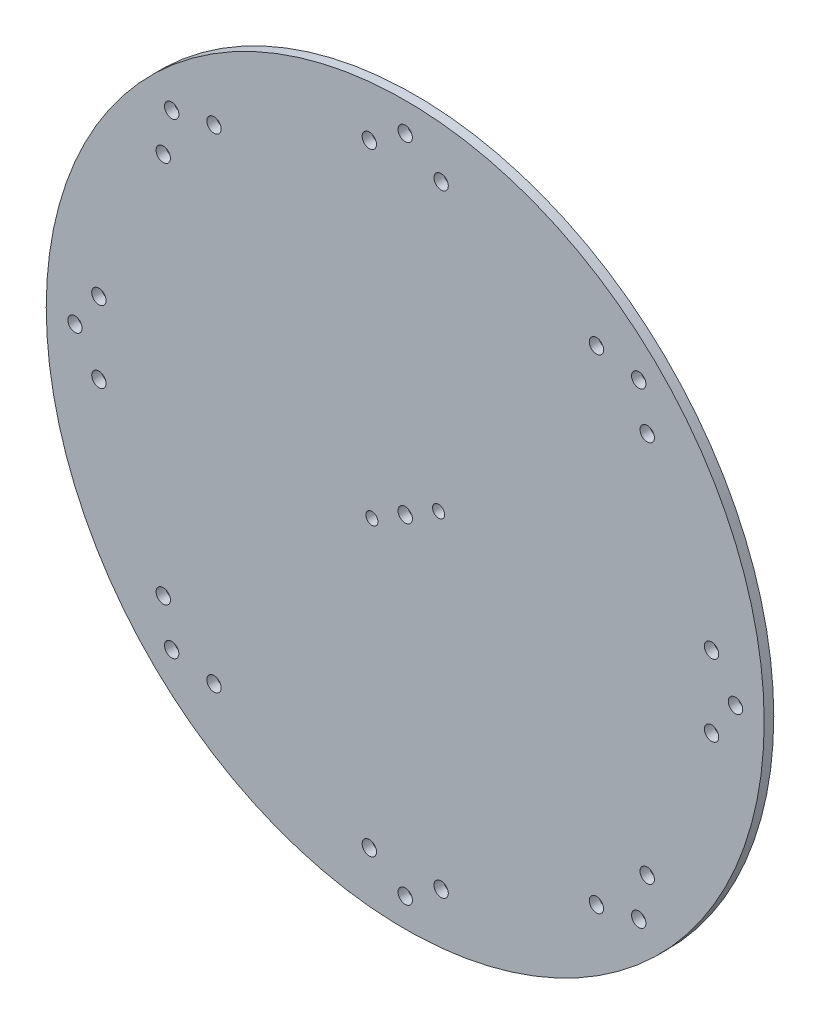
SolidWorks part; units mm, degrees
ref_plane "Front Plane" through (0, 0, 0) normal (0, 0, 1) x (1, 0, 0)
ref_plane "Top Plane" through (0, 0, 0) normal (0, 1, 0) x (1, 0, 0)
ref_plane "Right Plane" through (0, 0, 0) normal (1, 0, 0) x (0, 0, -1)
sketch "Sketch1" plane through (0, 0, 0) normal (0, 0, 1) x (1, 0, 0)
  line L0 (81.9, 0) -> (-68.1, 0) construction
  line L2 (9.3, 1.8) -> (9.3, -1.8)
  circle A0 centre (6.9, 0) radius 75
  arc A5 (9.3, 1.8) -> (9.3, -1.8) centre (6.9, 0) ccw construction
  arc A6 (9.3, 1.8) -> (9.3, -1.8) centre (6.9, 0) ccw
  point P10 (70.9, 0)
  dimension "D1" = 150
extrude "Boss-Extrude3" add sketch "Sketch1" along normal blind 2
sketch "Sketch2" plane through (0, 0, 2) normal (0, 0, 1) x (1, 0, 0)
  line L0 (81.9, 0) -> (-68.1, 0) construction
  line L1 (6.9, 0) -> (6.9, -75) construction
  line L2 (70.9, 7.5) -> (70.9, -7.5)
  line L3 (9.3, -1.8) -> (9.3, 1.8) construction
  circle A0 centre (6.9, 0) radius 75 construction
  circle A1 centre (75.9, 0) radius 1.5
  circle A2 centre (70.9, -7.5) radius 1.5
  circle A5 centre (70.9, 7.5) radius 1.5
  point P12 (70.9, 0)
  dimension "D1" = 3
  dimension "D2" = 6
  dimension "D3" = 15
  dimension "D4" = 5
extrude "Cut-Extrude1" cut sketch "Sketch2" against normal blind 2
pattern_circular "CirPattern2" count 8 over 360 about axis through (6.9, 0, 0) along (0, 0, 1) of "Cut-Extrude1"
sketch "Sketch3" plane through (0, 0, 0) normal (0, 0, -1) x (-1, 0, 0)
  line L0 (-9.3, -1.8) -> (-9.3, 1.8) construction
  line L1 (-9.3, -1.8) -> (-9.3, 1.8)
  arc A0 (-9.3, -1.8) -> (-9.3, 1.8) centre (-6.9, 0) ccw construction
  arc A1 (-9.3, -1.8) -> (-9.3, 1.8) centre (-6.9, 0) ccw
  circle A2 centre (-6.9, 0) radius 1.5
extrude "Boss-Extrude4" add sketch "Sketch3" against normal up to surface (2 mm away) up to face at (6.9, -70.5, 2)
sketch "Sketch4" plane through (0, 0, 2) normal (0, 0, 1) x (1, 0, 0)
  circle A0 centre (13.8683, 4.1295) radius 1.2648
  circle A1 centre (-0.0683, -4.1295) radius 1.2648
extrude "Cut-Extrude2" cut sketch "Sketch4" against normal blind 10
